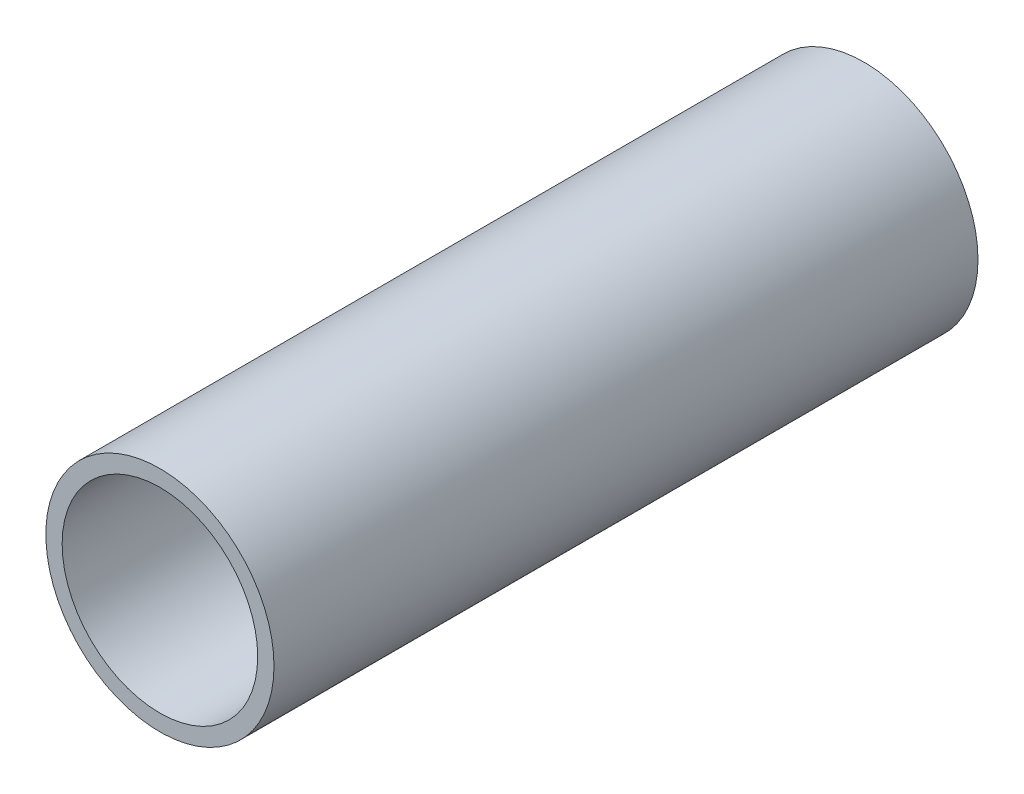
SolidWorks part; units mm, degrees
ref_plane "Face" through (0, 0, 0) normal (0, 0, 1) x (1, 0, 0)
ref_plane "Dessus" through (0, 0, 0) normal (0, 1, 0) x (1, 0, 0)
ref_plane "Droite" through (0, 0, 0) normal (1, 0, 0) x (0, 0, -1)
sketch "Esquisse1" plane through (0, 0, 0) normal (0, 0, 1) x (1, 0, 0)
  circle A0 centre (0, 0) radius 1.75
  circle A1 centre (0, 0) radius 1.5
  dimension "D1" = 3.5
  dimension "D2" = 3
extrude "Base-Extrusion" add sketch "Esquisse1" against normal blind 10.8
